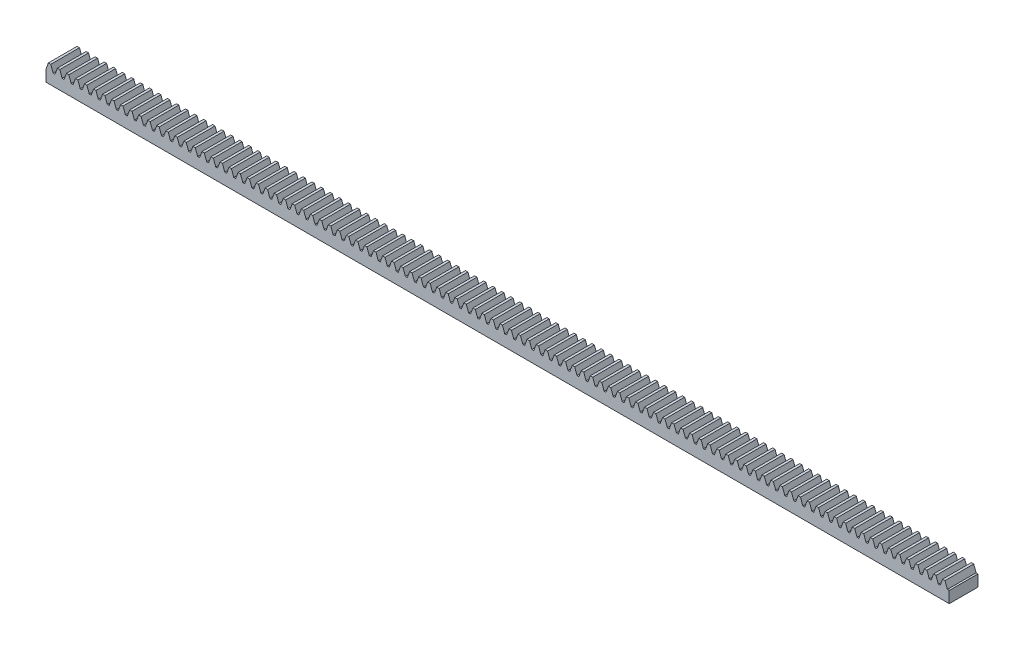
SolidWorks part; units mm, degrees
ref_plane "前视基准面" through (0, 0, 0) normal (0, 0, 1) x (1, 0, 0)
ref_plane "上视基准面" through (0, 0, 0) normal (0, 1, 0) x (1, 0, 0)
ref_plane "右视基准面" through (0, 0, 0) normal (1, 0, 0) x (0, 0, -1)
sketch "草图1" plane through (0, 0, 0) normal (0, 0, 1) x (1, 0, 0)
  line L1 (0, 0) -> (628.3185, 0)
  line L2 (0, 0) -> (0, -7.95)
  line L3 (0, -7.95) -> (628.3185, -7.95)
  line L4 (628.3185, 0) -> (628.3185, -7.95)
  dimension "D1" = 7.95
  dimension "L" = 628.3185
extrude "拉伸1" add sketch "草图1" along normal blind 20
sketch "草图2" plane through (0, 0, 20) normal (0, 0, 1) x (1, 0, 0)
  line L0 (0, 0) -> (1.6379, 4.5)
  line L1 (1.6379, 4.5) -> (3.3236, 4.5)
  line L2 (3.3236, 4.5) -> (4.9614, 0)
  line L3 (628.3185, 0) -> (0, 0) construction
  line L4 (0, 0) -> (4.9614, 0)
  line L5 (0.9099, 2.5) -> (4.0515, 2.5) construction
  dimension "D2" = 70
  dimension "alpha" = 110
  dimension "ha" = 2
  dimension "hf" = 2.5
  dimension "S" = 3.1416
extrude "拉伸2" add sketch "草图2" against normal up to surface (20 mm away) up to face at (314.1593, -3.975, 0)
pattern_linear "阵列(线性)1" count 100 spacing 6.2832 along (1, 0, 0) of "拉伸2"
equation "\"d\"=\"S@草图2\" * 2"
equation "\"z\"= int(  \"L@草图1\" / (  \"S@草图2\" * 2 ) + 0.5 )"
